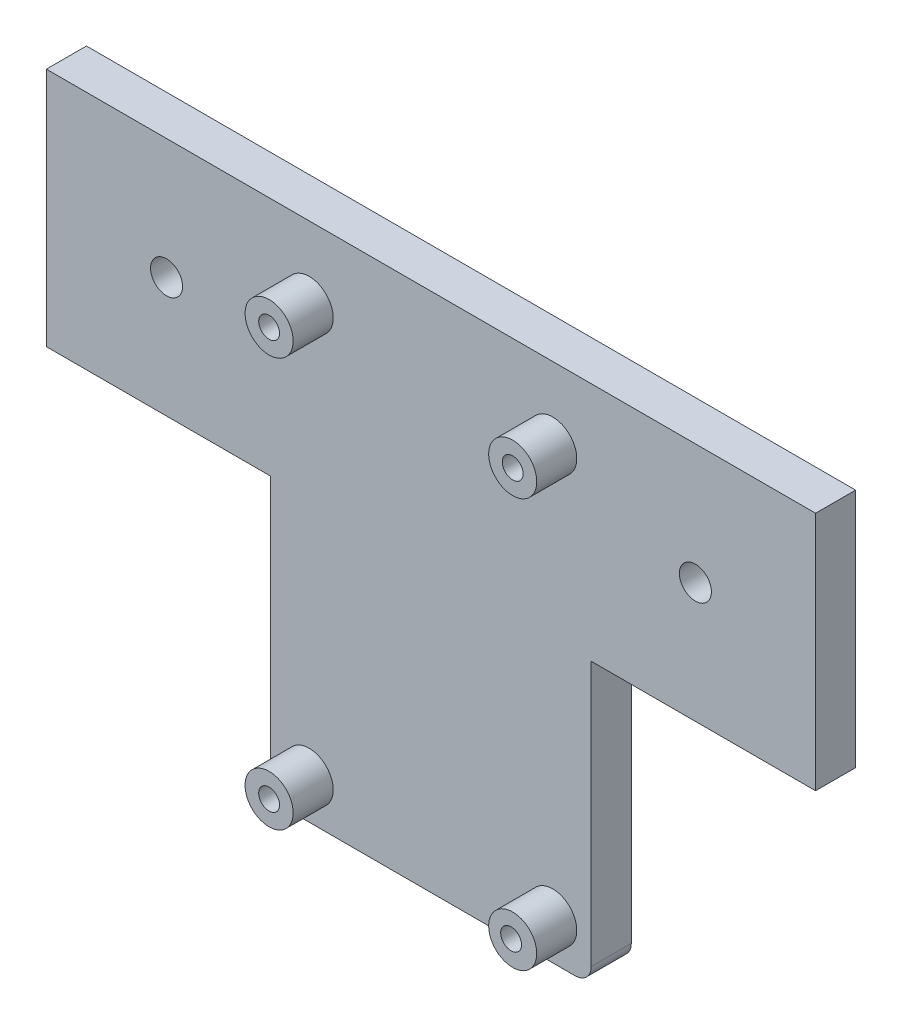
SolidWorks part; units mm, degrees
ref_plane "Płaszczyzna przednia" through (0, 0, 0) normal (0, 0, 1) x (1, 0, 0)
ref_plane "Płaszczyzna górna" through (0, 0, 0) normal (0, 1, 0) x (1, 0, 0)
ref_plane "Płaszczyzna prawa" through (0, 0, 0) normal (1, 0, 0) x (0, 0, -1)
sketch "Szkic1" plane through (0, 0, 0) normal (0, 0, 1) x (1, 0, 0)
  line L1 (0, 0) -> (96, 0)
  line L2 (0, 0) -> (0, 30)
  line L3 (0, 30) -> (96, 30)
  line L4 (96, 0) -> (96, 30)
extrude "Dodanie-wyciągnięcie1" add sketch "Szkic1" along normal blind 5
sketch "Szkic2" plane through (0, 0, 5) normal (0, 0, 1) x (1, 0, 0)
  line L0 (0, 0) -> (96, 0) construction
  line L1 (28, 0) -> (68, 0)
  line L2 (28, 0) -> (28, -35)
  line L3 (28, -35) -> (68, -35)
  line L4 (68, 0) -> (68, -35)
extrude "Dodanie-wyciągnięcie2" add sketch "Szkic2" against normal blind 5
sketch "Szkic3" plane through (0, 0, 5) normal (0, 0, 1) x (1, 0, 0)
  circle A0 centre (15, 15) radius 2
  circle A1 centre (81, 15) radius 2
extrude "Wytnij-wyciągnięcie1" cut sketch "Szkic3" against normal blind 5
sketch "Szkic4" plane through (0, 0, 5) normal (0, 0, 1) x (1, 0, 0)
  circle A0 centre (32.8, -30) radius 3
  circle A1 centre (63.2, -30) radius 3
  circle A2 centre (63.2, 21) radius 3
  circle A3 centre (32.8, 21) radius 3
  point P8 (0, 0)
  point P9 (0, 0)
  point P10 (0, 0)
  point P11 (0, 0)
  point P12 (0, 0)
extrude "Dodanie-wyciągnięcie3" add sketch "Szkic4" along normal blind 5
sketch "Szkic5" plane through (0, 0, 10) normal (0, 0, 1) x (1, 0, 0)
  circle A0 centre (32.8, 21) radius 1.3
  circle A2 centre (63.2, 21) radius 1.3
  circle A3 centre (32.8, -30) radius 1.3
  circle A4 centre (63, -30) radius 1.3
extrude "Wytnij-wyciągnięcie2" cut sketch "Szkic5" against normal blind 7
fillet "Zaokrąglenie1" radius 2 2 edges at (28, -35, 2.5) (68, -35, 2.5)
